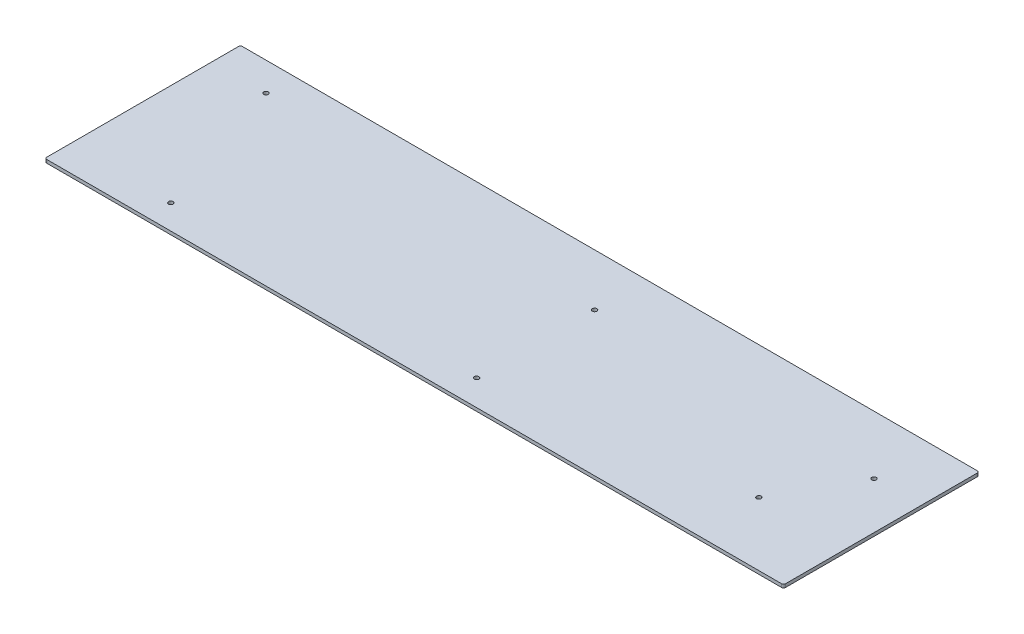
SolidWorks part; units mm, degrees
ref_plane "Front Plane" through (0, 0, 0) normal (0, 0, 1) x (1, 0, 0)
ref_plane "Top Plane" through (0, 0, 0) normal (0, 1, 0) x (1, 0, 0)
ref_plane "Right Plane" through (0, 0, 0) normal (1, 0, 0) x (0, 0, -1)
sketch "Sketch1" plane through (0, 0, 0) normal (0, 1, 0) x (1, 0, 0)
  line L1 (-178.825, 47.625) -> (178.825, 47.625)
  line L2 (-179.825, 46.625) -> (-179.825, -46.625)
  line L3 (-178.825, -47.625) -> (178.825, -47.625)
  line L4 (179.825, 46.625) -> (179.825, -46.625)
  line L5 (-179.825, 47.625) -> (179.825, -47.625) construction
  line L6 (-179.825, -47.625) -> (179.825, 47.625) construction
  arc A0 (178.825, -47.625) -> (179.825, -46.625) centre (178.825, -46.625) ccw
  arc A1 (178.825, 47.625) -> (179.825, 46.625) centre (178.825, 46.625) cw
  arc A2 (-179.825, -46.625) -> (-178.825, -47.625) centre (-178.825, -46.625) ccw
  arc A3 (-178.825, 47.625) -> (-179.825, 46.625) centre (-178.825, 46.625) ccw
  circle A4 centre (157.075, 19.175) radius 1.1
  circle A5 centre (136.925, -16.775) radius 1.1
  circle A6 centre (-153.475, 33.725) radius 1.1
  circle A7 centre (17.925, 22.275) radius 1.1
  circle A8 centre (17.875, -35.075) radius 1.1
  circle A9 centre (-130.375, -35.725) radius 1.1
  point P0 (0, 0)
  dimension "D3" = 1
  dimension "D4" = 2.2
  dimension "D7" = 2.2
  dimension "D8" = 2.2
  dimension "D9" = 2.2
  dimension "D10" = 2.2
  dimension "D11" = 2.2
  dimension "D1" = 359.65
  dimension "D2" = 95.25
  dimension "D5" = 22.75
  dimension "D6" = 28.45
  dimension "D12" = 42.9
  dimension "D13" = 30.85
  dimension "D14" = 25.35
  dimension "D15" = 161.9
  dimension "D16" = 12.55
  dimension "D17" = 161.95
  dimension "D18" = 11.9
  dimension "D19" = 49.45
  dimension "D20" = 13.9
  dimension "D21" = 26.35
extrude "Boss-Extrude1" add sketch "Sketch1" along normal blind 1.6
